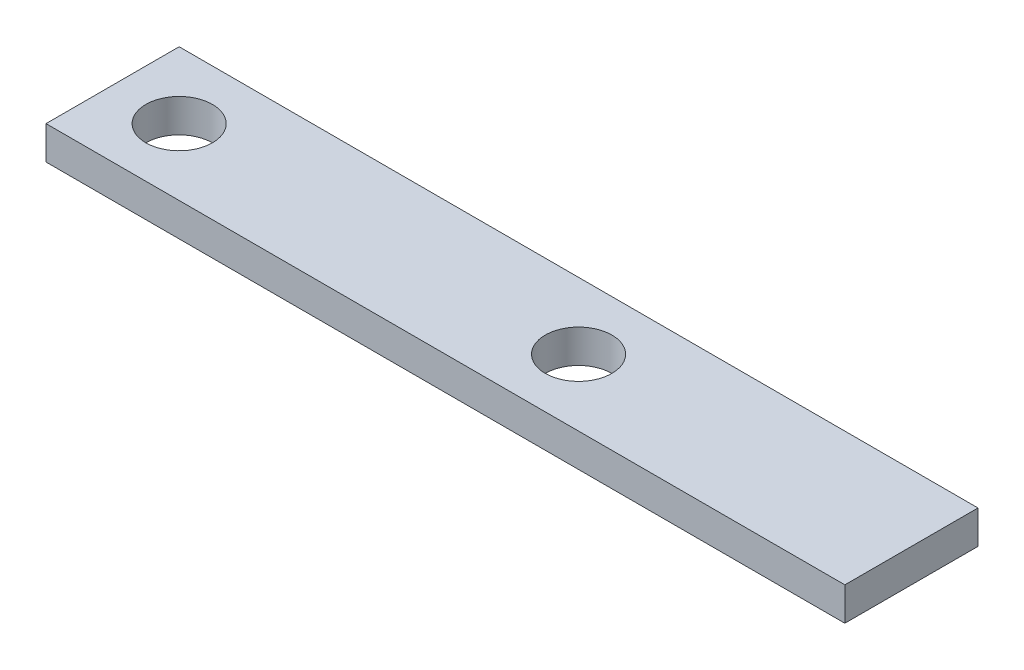
SolidWorks part; units mm, degrees
ref_plane "Front Plane" through (0, 0, 0) normal (0, 0, 1) x (1, 0, 0)
ref_plane "Top Plane" through (0, 0, 0) normal (0, 1, 0) x (1, 0, 0)
ref_plane "Right Plane" through (0, 0, 0) normal (1, 0, 0) x (0, 0, -1)
sketch "Sketch1" plane through (0, 0, 0) normal (0, 1, 0) x (1, 0, 0)
  line L10 (0, 0) -> (76.2, 0)
  line L11 (0, 0) -> (0, 12.7)
  line L12 (76.2, 0) -> (76.2, 12.7)
  line L13 (0, 12.7) -> (76.2, 12.7)
  circle A0 centre (6.35, 6.35) radius 3.175
  circle A1 centre (44.45, 6.35) radius 3.175
  dimension "D1" = 12.7
  dimension "D2" = 76.2
extrude "Boss-Extrude2" add sketch "Sketch1" along normal blind 3.175
